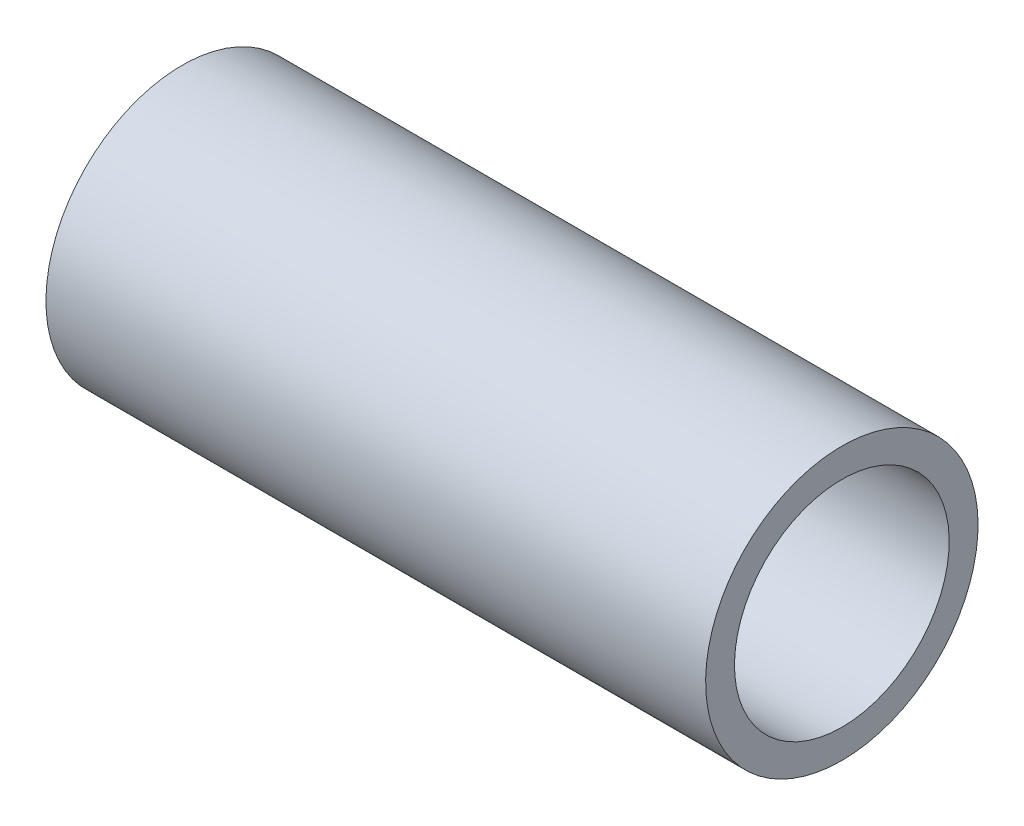
SolidWorks part; units mm, degrees
material "Nichel"
ref_plane "Piano frontale" through (0, 0, 0) normal (0, 0, 1) x (1, 0, 0)
ref_plane "Piano superiore" through (0, 0, 0) normal (0, 1, 0) x (1, 0, 0)
ref_plane "Piano destro" through (0, 0, 0) normal (1, 0, 0) x (0, 0, -1)
sketch "Schizzo1" plane through (0, 0, 0) normal (0, 0, 1) x (1, 0, 0)
  line L5 (-57.15, 18.6) -> (57.15, 18.6)
  line L9 (-57.15, 18.6) -> (0, 0) construction
  line L10 (0, 0) -> (57.15, 18.6) construction
  line L11 (-57.15, 18.6) -> (57.15, 18.6)
  line L12 (-57.15, 18.6) -> (-57.15, 23.6)
  line L13 (-57.15, 23.6) -> (57.15, 23.6)
  line L14 (57.15, 18.6) -> (57.15, 23.6)
  point P0 (0, 0)
  dimension "D1" = 114.3
  dimension "D2" = 18.6
  dimension "D3" = 5
sketch "Schizzo2" plane through (0, 0, 0) normal (0, 0, 1) x (1, 0, 0)
  line L0 (-66.6613, 0) -> (66.6613, 0)
revolve "Rivoluzione1" add sketch "Schizzo1" angle 360 about L0
